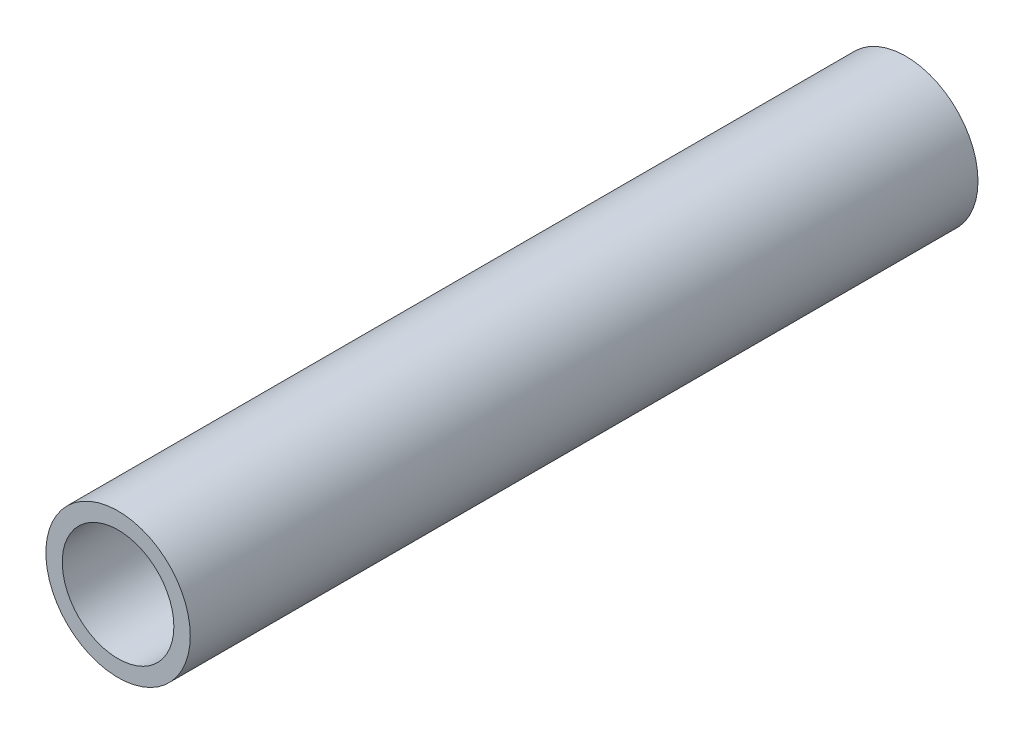
SolidWorks part; units mm, degrees
material "PVC 0.007 Plasticized"
ref_plane "Front Plane" through (0, 0, 0) normal (0, 0, 1) x (1, 0, 0)
ref_plane "Top Plane" through (0, 0, 0) normal (0, 1, 0) x (1, 0, 0)
ref_plane "Right Plane" through (0, 0, 0) normal (1, 0, 0) x (0, 0, -1)
sketch "Sketch1" plane through (0, 0, 0) normal (0, 0, 1) x (1, 0, 0)
  circle A0 centre (0, 0) radius 11
  circle A2 centre (0, 0) radius 8.5
  dimension "D1" = 2.5
extrude "Boss-Extrude1" add sketch "Sketch1" along normal blind 120
